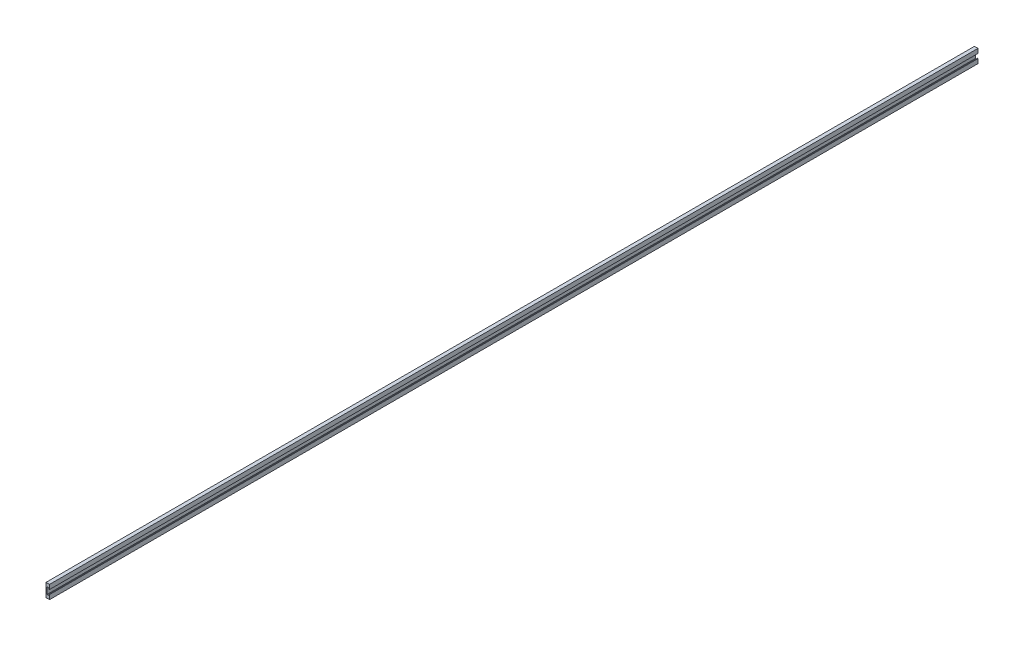
SolidWorks part; units mm, degrees
ref_plane "Front Plane" through (0, 0, 0) normal (0, 0, 1) x (1, 0, 0)
ref_plane "Top Plane" through (0, 0, 0) normal (0, 1, 0) x (1, 0, 0)
ref_plane "Right Plane" through (0, 0, 0) normal (1, 0, 0) x (0, 0, -1)
sketch "Sketch1" plane through (0, 0, 0) normal (0, 0, 1) x (1, 0, 0)
  line L0 (0, 0) -> (-8, 0)
  line L1 (-8, 0) -> (-8, 30)
  line L2 (-8, 30) -> (0, 30)
  line L3 (0, 30) -> (0, 22.5)
  line L4 (-1.5, 22.5) -> (-5.5, 22.5)
  line L5 (-5.5, 22.5) -> (-5.5, 7.5)
  line L6 (-5.5, 7.5) -> (-1.5, 7.5)
  line L7 (0, 7.5) -> (0, 0)
  line L8 (-8, 15) -> (6.9942, 15) construction
  line L9 (0, 22.5) -> (0, 20)
  line L10 (0, 20) -> (-1.5, 20)
  line L11 (-1.5, 20) -> (-1.5, 22.5)
  line L12 (0, 7.5) -> (0, 10)
  line L13 (0, 10) -> (-1.5, 10)
  line L14 (-1.5, 10) -> (-1.5, 7.5)
  dimension "D1" = 30
  dimension "D2" = 15
  dimension "D3" = 5.5
  dimension "D4" = 8
  dimension "D5" = 1.5
  dimension "D6" = 2.5
extrude "Boss-Extrude1" add sketch "Sketch1" along normal mid plane 2100
